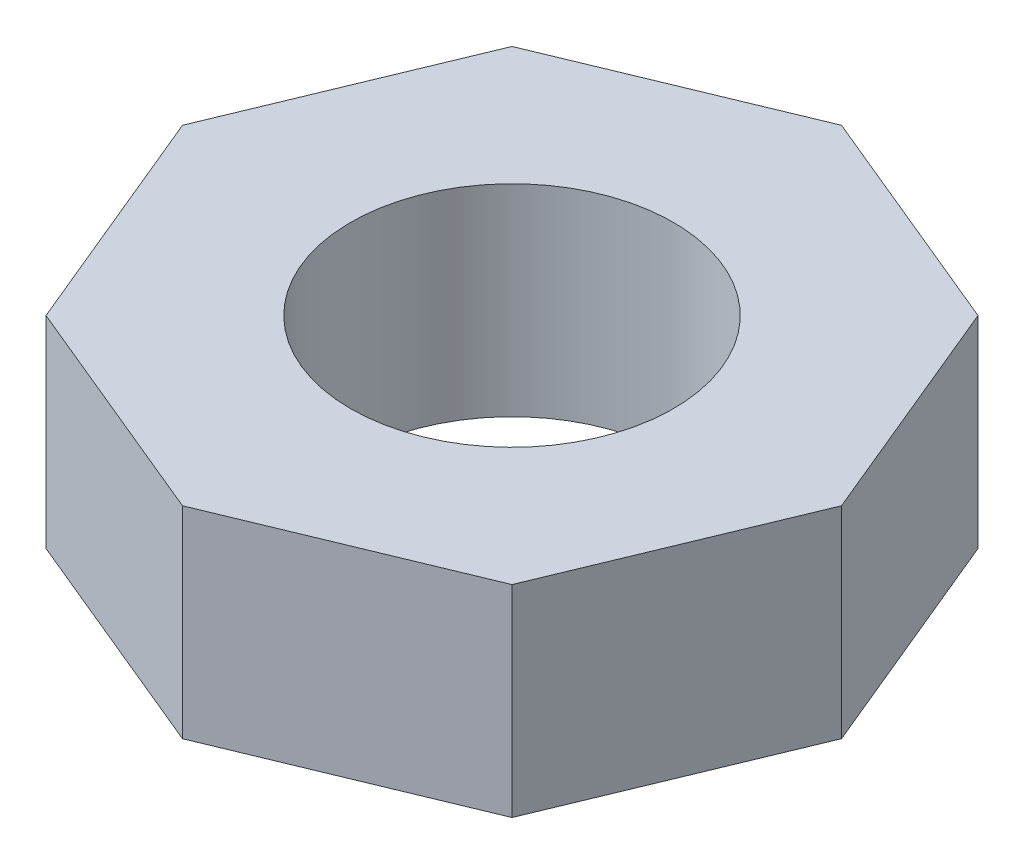
SolidWorks part; units mm, degrees
ref_plane "Front" through (0, 0, 0) normal (0, 0, 1) x (1, 0, 0)
ref_plane "Top" through (0, 0, 0) normal (0, 1, 0) x (1, 0, 0)
ref_plane "Right" through (0, 0, 0) normal (1, 0, 0) x (0, 0, -1)
sketch "Sketch1" plane through (0, 0, 0) normal (0, 1, 0) x (1, 0, 0)
  line L1 (3.2664, 0) -> (2.3097, 2.3097)
  line L2 (2.3097, 2.3097) -> (0, 3.2664)
  line L3 (0, 3.2664) -> (-2.3097, 2.3097)
  line L4 (-2.3097, 2.3097) -> (-3.2664, 0)
  line L5 (-3.2664, 0) -> (-2.3097, -2.3097)
  line L6 (-2.3097, -2.3097) -> (0, -3.2664)
  line L7 (0, -3.2664) -> (2.3097, -2.3097)
  line L8 (2.3097, -2.3097) -> (3.2664, 0)
  circle A0 centre (0, 0) radius 3.0178 construction
  circle A1 centre (0, 0) radius 1.6
extrude "Boss-Extrude1" add sketch "Sketch1" along normal blind 2
